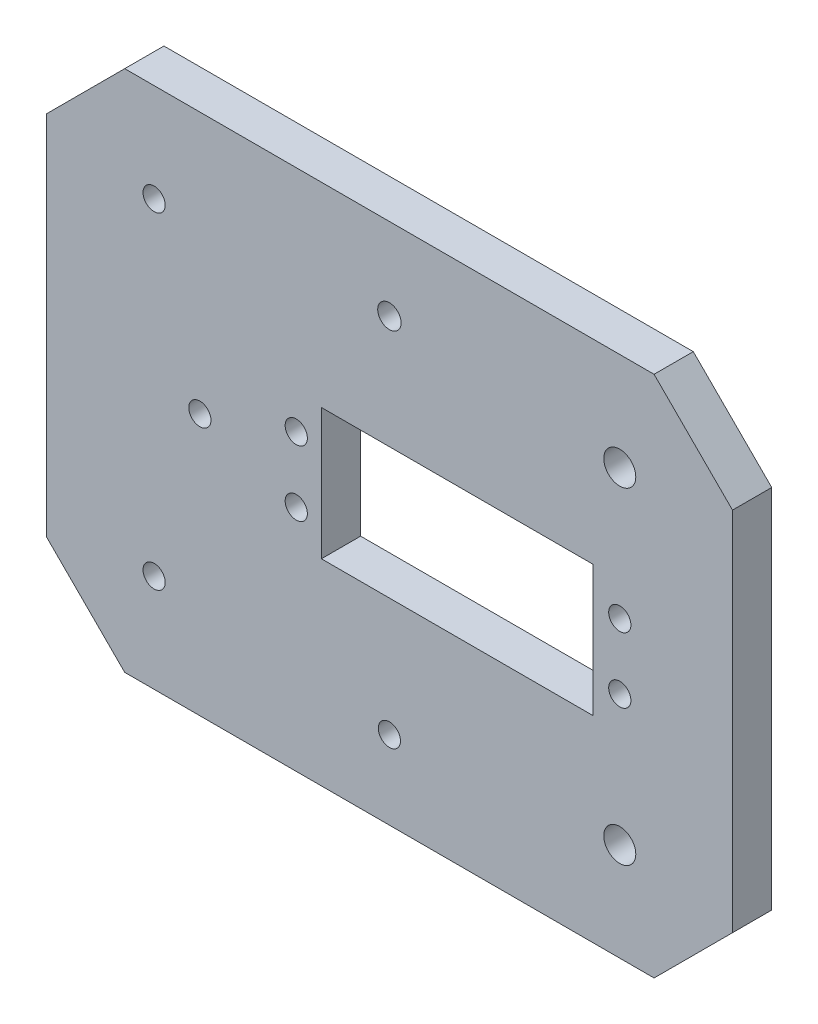
SolidWorks part; units mm, degrees
ref_plane "Спереди" through (0, 0, 0) normal (0, 0, 1) x (1, 0, 0)
ref_plane "Сверху" through (0, 0, 0) normal (0, 1, 0) x (1, 0, 0)
ref_plane "Справа" through (0, 0, 0) normal (1, 0, 0) x (0, 0, -1)
other "Configuration Table"
sketch "Эскиз1" plane through (0, 0, 0) normal (0, 0, 1) x (1, 0, 0)
  line L0 (-40.5, -40) -> (40.5, -40)
  line L1 (40.5, -40) -> (52.5, -28)
  line L2 (52.5, -28) -> (52.5, 28)
  line L3 (52.5, 28) -> (40.5, 40)
  line L4 (40.5, 40) -> (-40.5, 40)
  line L5 (-40.5, 40) -> (-52.5, 28)
  line L6 (-52.5, 28) -> (-52.5, -28)
  line L7 (-52.5, -28) -> (-40.5, -40)
  line L9 (-10.4, -9.9) -> (31.15, -9.9)
  line L10 (-10.4, -9.9) -> (-10.4, 10.15)
  line L11 (-10.4, 10.15) -> (31.15, 10.15)
  line L12 (31.15, -9.9) -> (31.15, 10.15)
  circle A0 centre (-14.25, -5) radius 1.7
  circle A1 centre (-14.25, 5) radius 1.7
  circle A2 centre (35.25, -5) radius 1.7
  circle A3 centre (35.25, 5) radius 1.7
  circle A4 centre (-36, -25) radius 1.7
  circle A5 centre (-36, 25) radius 1.7
  circle A6 centre (35.25, -25) radius 2.45
  circle A7 centre (35.25, 25) radius 2.45
  circle A8 centre (0, 27.45) radius 1.7868
  circle A9 centre (0, -28) radius 1.7
  circle A10 centre (-29, 0) radius 1.7
extrude "02_Pan_servo_deck" add sketch "Эскиз1" along normal blind 6
